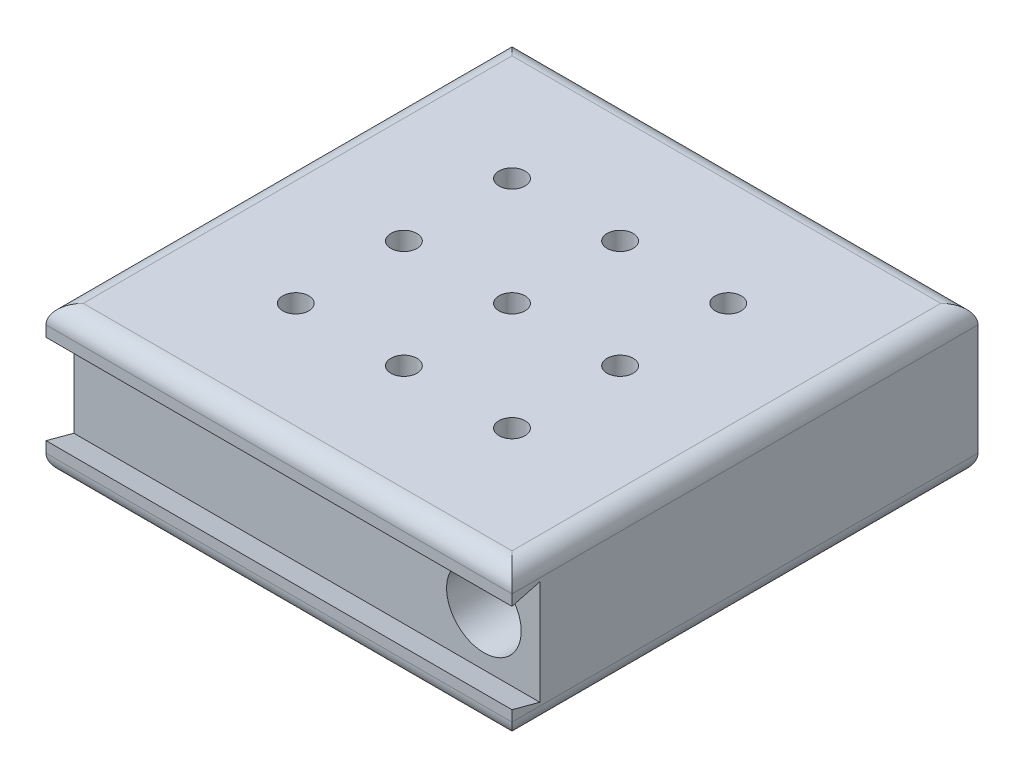
SolidWorks part; units mm, degrees
ref_plane "Front Plane" through (0, 0, 0) normal (0, 0, 1) x (1, 0, 0)
ref_plane "Top Plane" through (0, 0, 0) normal (0, 1, 0) x (1, 0, 0)
ref_plane "Right Plane" through (0, 0, 0) normal (1, 0, 0) x (0, 0, -1)
sketch "Sketch1" plane through (0, 0, 0) normal (0, 1, 0) x (1, 0, 0)
  line L1 (0, 0) -> (125, 0)
  line L2 (0, 0) -> (0, 125)
  line L3 (0, 125) -> (125, 125)
  line L4 (125, 0) -> (125, 125)
  dimension "D1" = 125
  dimension "D2" = 125
extrude "Boss-Extrude1" add sketch "Sketch1" along normal blind 39.8
sketch "Sketch2" plane through (125, 0, 0) normal (1, 0, 0) x (0, 0, -1)
  line L0 (0, 31.9) -> (7.4641, 33.9)
  line L1 (0, 39.8) -> (0, 0) construction
  line L2 (7.4641, 33.9) -> (7.4641, 5.9)
  line L3 (7.4641, 5.9) -> (0, 7.9)
  line L4 (0, 7.9) -> (0, 31.9)
  line L5 (-11.5901, 19.9) -> (144.8437, 19.9) construction
  line L6 (0, 39.8) -> (125, 39.8) construction
  line L7 (0, 0) -> (125, 0) construction
  dimension "D1" = 28
  dimension "D2" = 24
  dimension "D3" = 105
extrude "Cut-Extrude1" cut sketch "Sketch2" against normal blind 132.8
sketch "Sketch3" plane through (0, 0, -7.4641) normal (0, 0, 1) x (1, 0, 0)
  line L0 (125, 5.9) -> (125, 33.9) construction
  line L3 (-10.5699, 19.9) -> (142.9202, 19.9) construction
  line L4 (0, 39.8) -> (125, 39.8) construction
  line L5 (0, 0) -> (125, 0) construction
  circle A0 centre (110, 19.9) radius 10
  dimension "D1" = 15
  dimension "D2" = 20
extrude "Cut-Extrude2" cut sketch "Sketch3" against normal blind 40 contours A0
fillet "Fillet1" radius 5 4 edges at (62.5, 39.8, -125) (125, 39.8, -62.5) (62.5, 39.8, 0) (0, 39.8, -62.5)
fillet "Fillet2" radius 5 4 edges at (62.5, 0, 0) (125, 0, -62.5) (62.5, 0, -125) (0, 0, -62.5)
sketch "Sketch4" plane through (0, 39.8, 0) normal (0, 1, 0) x (1, 0, 0)
  line L0 (0, 125) -> (125, 125) construction
  line L2 (33.5, 91.5) -> (91.5, 91.5) construction
  line L3 (33.5, 91.5) -> (33.5, 33.5) construction
  line L4 (62.5, 91.5) -> (62.5, 33.5) construction
  line L5 (91.5, 91.5) -> (91.5, 33.5) construction
  line L7 (0, 0) -> (0, 125) construction
  line L8 (125, 125) -> (125, 0) construction
  line L10 (33.5, 62.5) -> (91.5, 62.5) construction
  line L11 (125, 0) -> (0, 0) construction
  circle A0 centre (33.5, 91.5) radius 3.5
  circle A1 centre (62.5, 91.5) radius 3.5
  circle A2 centre (91.5, 91.5) radius 3.5
  circle A3 centre (33.5, 62.5) radius 3.5
  circle A4 centre (62.5, 62.5) radius 3.5
  circle A5 centre (91.5, 62.5) radius 3.5
  circle A6 centre (33.5, 33.5) radius 3.5
  circle A7 centre (62.5, 33.5) radius 3.5
  circle A8 centre (91.5, 33.5) radius 3.5
  dimension "D3" = 7
  dimension "D4" = 29
  dimension "D5" = 29
  dimension "D7" = 29
extrude "Cut-Extrude3" cut sketch "Sketch4" against normal blind 22
